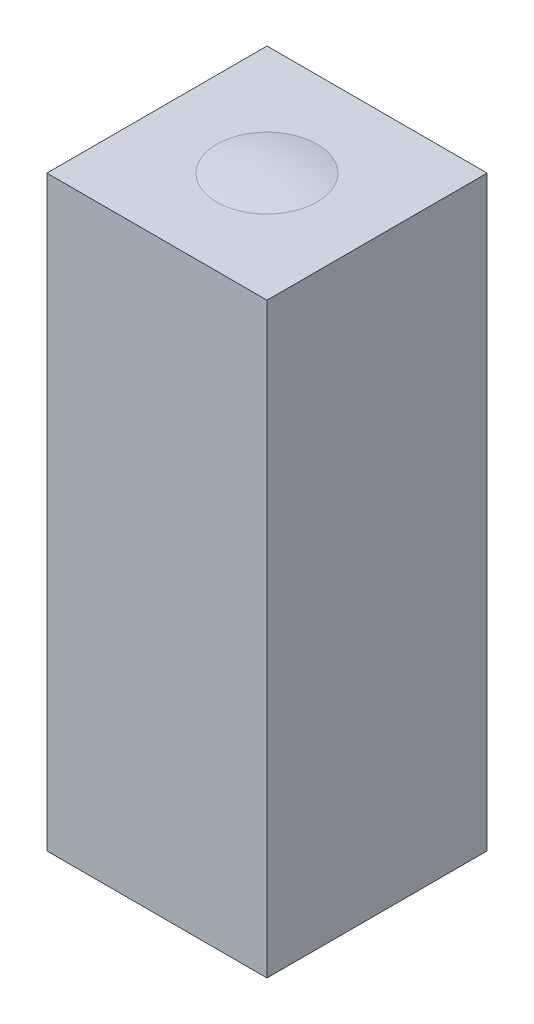
SolidWorks part; units mm, degrees
ref_plane "Front Plane" through (0, 0, 0) normal (0, 0, 1) x (1, 0, 0)
ref_plane "Top Plane" through (0, 0, 0) normal (0, 1, 0) x (1, 0, 0)
ref_plane "Right Plane" through (0, 0, 0) normal (1, 0, 0) x (0, 0, -1)
sketch "Sketch1" plane through (0, 0, 0) normal (0, 1, 0) x (1, 0, 0)
  line L1 (-12.7119, 17.161) -> (-42.7119, 17.161)
  line L2 (-12.7119, 17.161) -> (-12.7119, -12.839)
  line L3 (-12.7119, -12.839) -> (-42.7119, -12.839)
  line L4 (-42.7119, 17.161) -> (-42.7119, -12.839)
  dimension "D1" = 30
  dimension "D2" = 30
extrude "Boss-Extrude1" add sketch "Sketch1" against normal blind 80 contours L1 L4 L3 L2
ref_plane "Plane1" through (0, -40, 0) normal (0, 1, 0) x (1, 0, 0)
ref_plane "Plane2" through (-27.7119, 0, 0) normal (-1, 0, 0) x (0, 0, 1)
ref_plane "Plane3" through (0, 0, -2.161) normal (0, 0, -1) x (-1, 0, 0)
sketch "Sketch2" plane through (0, 0, -2.161) normal (0, 0, -1) x (-1, 0, 0)
  line L0 (12.7119, 0) -> (42.7119, 0) construction
  line L1 (27.7119, -16.5) -> (27.7119, 16.5) construction
  line L2 (27.7119, 0) -> (34.5518, 0)
  line L3 (27.7119, 0) -> (27.7119, 0.7471)
  arc A0 (27.7119, 0.7471) -> (34.5518, 0) centre (27.7119, -30.9366) cw
ref_axis "Axis1" through (-27.7119, -84, -2.161) along (0, 1, 0)
revolve "Revolve4" add sketch "Sketch2" angle 360 about axis through (-27.7119, -84, -2.161) along (0, 1, 0)
